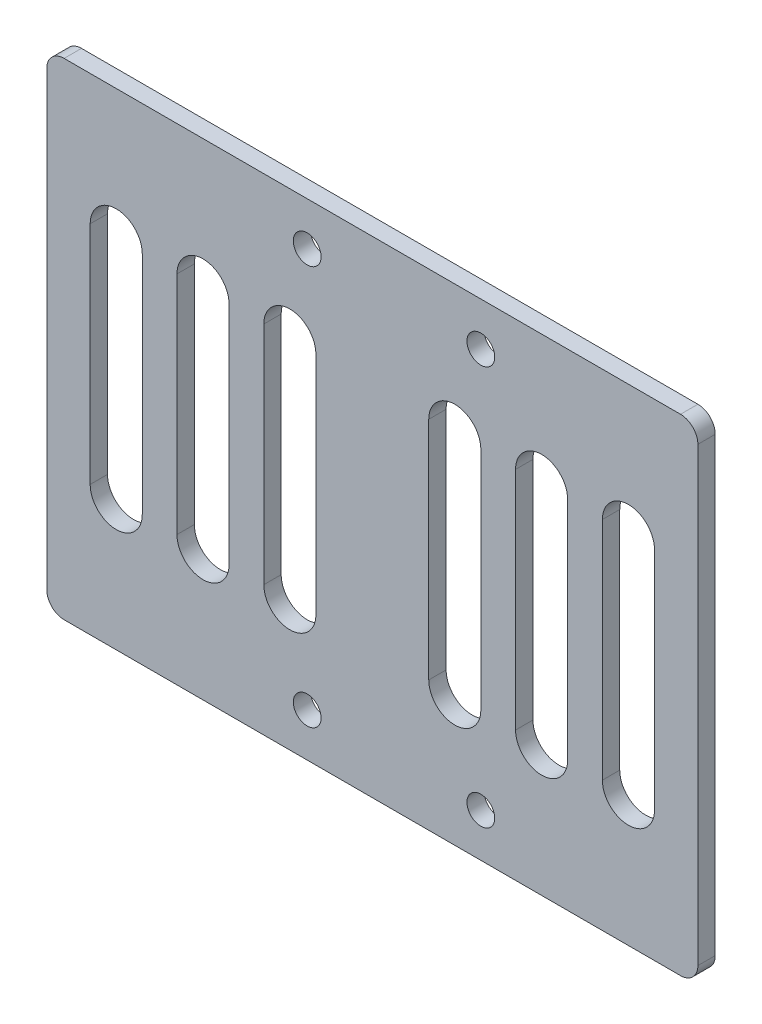
SolidWorks part; units mm, degrees
material "Thornel Mat VMA"
ref_plane "前视基准面" through (0, 0, 0) normal (0, 0, 1) x (1, 0, 0)
ref_plane "上视基准面" through (0, 0, 0) normal (0, 1, 0) x (1, 0, 0)
ref_plane "右视基准面" through (0, 0, 0) normal (1, 0, 0) x (0, 0, -1)
sketch "草图1" plane through (0, 0, 0) normal (0, 0, 1) x (1, 0, 0)
  line L0 (0, 0) -> (22.8646, 0) construction
  line L1 (37.5, -28) -> (-37.5, -28)
  line L2 (37.5, -28) -> (37.5, 28)
  line L3 (37.5, 28) -> (-37.5, 28)
  line L4 (-37.5, -28) -> (-37.5, 28)
  line L5 (37.5, -28) -> (-37.5, 28) construction
  line L6 (37.5, 28) -> (-37.5, -28) construction
  line L7 (29.5, 13) -> (29.5, -13) construction
  line L8 (32.5, 13) -> (32.5, -13)
  line L9 (26.5, 13) -> (26.5, -13)
  line L10 (19.5, 13) -> (19.5, -13) construction
  line L11 (22.5, 13) -> (22.5, -13)
  line L12 (16.5, 13) -> (16.5, -13)
  line L13 (9.5, 13) -> (9.5, -13) construction
  line L14 (12.5, 13) -> (12.5, -13)
  line L15 (6.5, 13) -> (6.5, -13)
  line L16 (0, 0) -> (0, 13) construction
  line L17 (-9.5, 13) -> (-9.5, -13) construction
  line L18 (-12.5, 13) -> (-12.5, -13)
  line L19 (-6.5, 13) -> (-6.5, -13)
  line L20 (-19.5, 13) -> (-19.5, -13) construction
  line L21 (-22.5, 13) -> (-22.5, -13)
  line L22 (-16.5, 13) -> (-16.5, -13)
  line L23 (-29.5, 13) -> (-29.5, -13) construction
  line L24 (-32.5, 13) -> (-32.5, -13)
  line L25 (-26.5, 13) -> (-26.5, -13)
  circle A0 centre (12.5, 23) radius 1.6
  circle A1 centre (-7.5, 23) radius 1.6
  circle A2 centre (-7.5, -23) radius 1.6
  circle A3 centre (12.5, -23) radius 1.6
  arc A4 (32.5, 13) -> (26.5, 13) centre (29.5, 13) ccw
  arc A5 (26.5, -13) -> (32.5, -13) centre (29.5, -13) ccw
  arc A6 (22.5, 13) -> (16.5, 13) centre (19.5, 13) ccw
  arc A7 (16.5, -13) -> (22.5, -13) centre (19.5, -13) ccw
  arc A8 (12.5, 13) -> (6.5, 13) centre (9.5, 13) ccw
  arc A9 (6.5, -13) -> (12.5, -13) centre (9.5, -13) ccw
  arc A10 (-12.5, 13) -> (-6.5, 13) centre (-9.5, 13) cw
  arc A11 (-6.5, -13) -> (-12.5, -13) centre (-9.5, -13) cw
  arc A12 (-22.5, 13) -> (-16.5, 13) centre (-19.5, 13) cw
  arc A13 (-16.5, -13) -> (-22.5, -13) centre (-19.5, -13) cw
  arc A14 (-32.5, 13) -> (-26.5, 13) centre (-29.5, 13) cw
  arc A15 (-26.5, -13) -> (-32.5, -13) centre (-29.5, -13) cw
  point P0 (0, 0)
  point P18 (29.5, 0)
  point P27 (19.5, 0)
  point P34 (9.5, 0)
  point P40 (-9.5, 0)
  point P47 (-19.5, 0)
  point P54 (-29.5, 0)
  dimension "D3" = 3.2
  dimension "D6" = 20
  dimension "D7" = 3.2
  dimension "D1" = 56
  dimension "D2" = 75
  dimension "D4" = 25
  dimension "D5" = 5
  dimension "D8" = 8
  dimension "D9" = 6
  dimension "D10" = 26
  dimension "D12" = 10
  dimension "D11" = 3
extrude "凸台-拉伸1" add sketch "草图1" along normal blind 2
fillet "圆角1" radius 2 4 edges at (37.5, -28, 1) (37.5, 28, 1) (-37.5, 28, 1) (-37.5, -28, 1)
